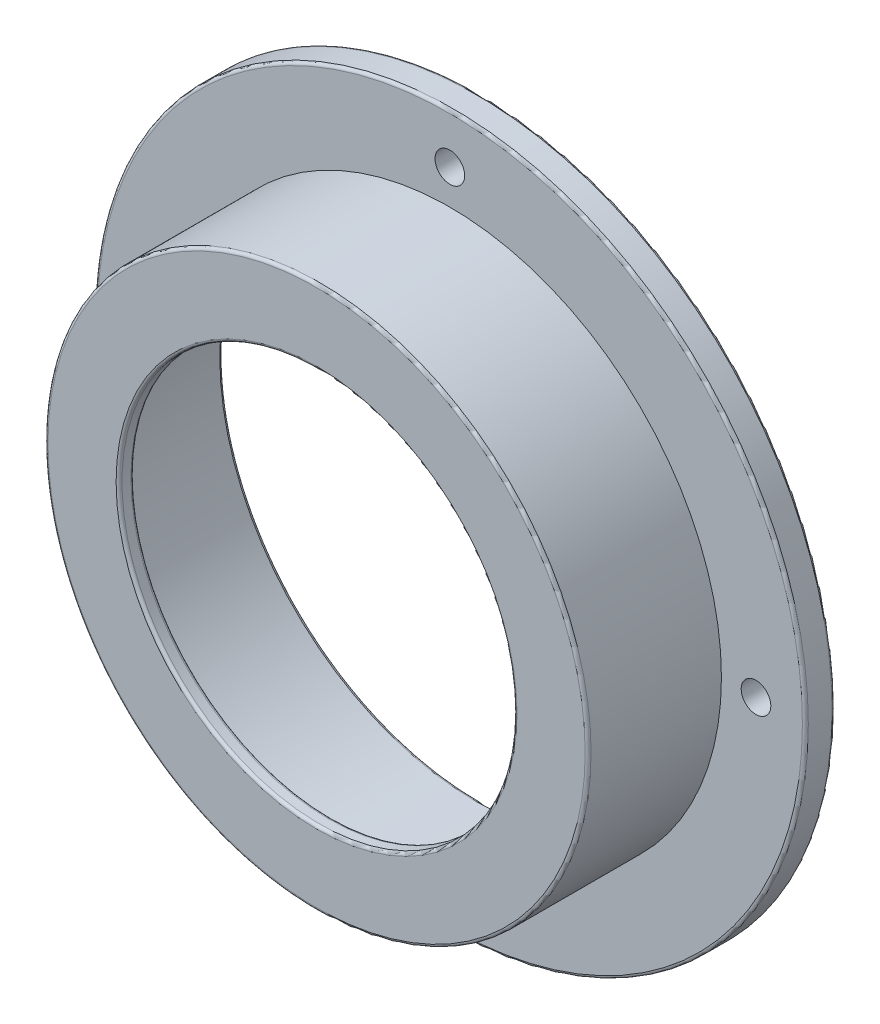
SolidWorks part; units mm, degrees
material "1060 合金"
ref_plane "前视基准面" through (0, 0, 0) normal (0, 0, 1) x (1, 0, 0)
ref_plane "上视基准面" through (0, 0, 0) normal (0, 1, 0) x (1, 0, 0)
ref_plane "右视基准面" through (0, 0, 0) normal (1, 0, 0) x (0, 0, -1)
sketch "草图1" plane through (0, 0, 0) normal (0, 0, 1) x (1, 0, 0)
  circle A0 centre (0, 0) radius 36
  dimension "D1" = 72
extrude "凸台-拉伸1" add sketch "草图1" along normal blind 3
sketch "草图2" plane through (0, 0, 3) normal (0, 0, 1) x (1, 0, 0)
  circle A0 centre (0, 0) radius 27.5
extrude "凸台-拉伸2" add sketch "草图2" along normal blind 12.5
sketch "草图3" plane through (0, 0, 0) normal (0, 0, -1) x (-1, 0, 0)
  circle A0 centre (0, 0) radius 26
extrude "切除-拉伸1" cut sketch "草图3" against normal blind 15
sketch "草图4" plane through (0, 0, 15.5) normal (0, 0, 1) x (1, 0, 0)
  circle A0 centre (0, 0) radius 27.5
extrude "凸台-拉伸3" add sketch "草图4" along normal blind 1
sketch "草图6" plane through (0, 0, 0) normal (0, 0, -1) x (-1, 0, 0)
  circle A0 centre (0, 31) radius 1.5
extrude "切除-拉伸3" cut sketch "草图6" against normal blind 3
pattern_circular "阵列(圆周)1" count 4 over 360 about axis through (0, 0, 0) along (0, 0, 1) of "切除-拉伸3"
sketch "草图7" plane through (0, 0, 16.5) normal (0, 0, 1) x (1, 0, 0)
  circle A0 centre (0, 0) radius 20
extrude "切除-拉伸4" cut sketch "草图7" against normal blind 10
fillet "圆角1" radius 0.3 6 edges at (-26, 0, 0) (27.5, 0, 16.5) (36, 0, 3) (36, 0, 0) (-20, 0, 15) (20, 0, 16.5)
